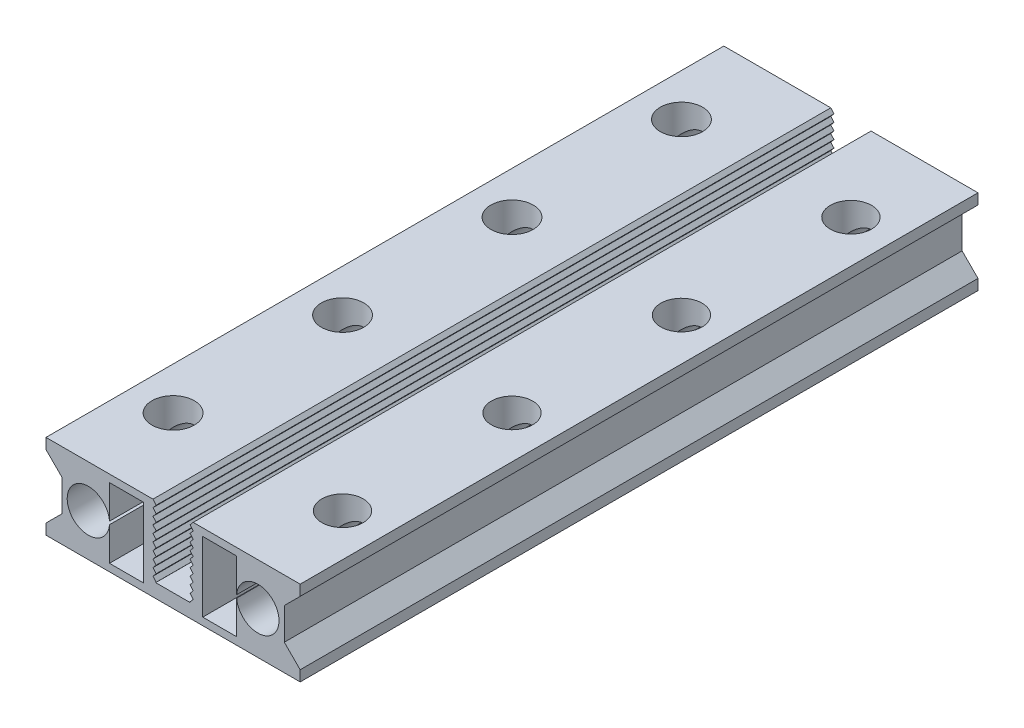
SolidWorks part; units mm, degrees
ref_plane "前视基准面" through (0, 0, 0) normal (0, 0, 1) x (1, 0, 0)
ref_plane "上视基准面" through (0, 0, 0) normal (0, 1, 0) x (1, 0, 0)
ref_plane "右视基准面" through (0, 0, 0) normal (1, 0, 0) x (0, 0, -1)
sketch "草图1" plane through (0, 0, 0) normal (0, 0, 1) x (1, 0, 0)
  line L0 (-12, 8) -> (-12, 7)
  line L1 (-12, 7) -> (-10.5, 5.5)
  line L2 (-10.5, 5.5) -> (-10.5, 2.5)
  line L3 (-10.5, 2.5) -> (-12, 1)
  line L4 (-12, 1) -> (-12, 0)
  line L5 (-12, 0) -> (12, 0)
  line L6 (12, 0) -> (12, 1)
  line L7 (12, 1) -> (10.5, 2.5)
  line L8 (10.5, 2.5) -> (10.5, 5.5)
  line L9 (10.5, 5.5) -> (12, 7)
  line L10 (12, 7) -> (12, 8)
  line L11 (12, 8) -> (1.9, 8)
  line L12 (0, 0) -> (0, 8) construction
  line L13 (-8, 4) -> (8, 4) construction
  line L14 (-1.9, 8) -> (-1.9, 1.3)
  line L15 (-6.005, 7.3) -> (-2.8, 7.3)
  line L16 (-6.005, 7.3) -> (-6.005, 4.1413)
  line L17 (-6.005, 0.7) -> (-2.8, 0.7)
  line L18 (-2.8, 7.3) -> (-2.8, 0.7)
  line L19 (-1.9, 1.3) -> (1.9, 1.3)
  line L20 (1.9, 1.3) -> (1.9, 8)
  line L21 (-1.9, 8) -> (-12, 8)
  line L22 (-6.005, 3.8587) -> (-6.005, 0.7)
  line L23 (2.8, 7.3) -> (6.005, 7.3)
  line L24 (2.8, 7.3) -> (2.8, 0.7)
  line L25 (2.8, 0.7) -> (6.005, 0.7)
  line L26 (6.005, 7.3) -> (6.005, 4.1413)
  line L27 (6.005, 3.8587) -> (6.005, 0.7)
  arc A0 (-6.005, 4.1413) -> (-6, 4) centre (-8, 4) ccw
  arc A1 (6.005, 3.8587) -> (6.005, 4.1413) centre (8, 4) ccw
  point P19 (10.5, 4)
  point P24 (-2.8, 4)
  point P27 (0, 1.3)
  dimension "D4" = 4
  dimension "D1" = 24
  dimension "D2" = 8
  dimension "D3" = 45
  dimension "D5" = 16
  dimension "D6" = 8
  dimension "D7" = 3
  dimension "D8" = 1
  dimension "D9" = 4
  dimension "D10" = 3.8
  dimension "D11" = 1.3
  dimension "D12" = 5.6
  dimension "D13" = 2.8
  dimension "D14" = 12.01
  dimension "D15" = 0.7
extrude "凸台-拉伸2" add sketch "草图1" along normal blind 64 contours L14 L21 L0 L1 L2 L3 L4 L5 L6 L7 L8 L9 L10 L11 L20 L19 A1 L27 L25 L24 L23 L26 A0 L16 L15 L18 L17 L22
sketch "草图3" plane through (0, 0, 64) normal (0, 0, 1) x (1, 0, 0)
  line L0 (-1.9, 8) -> (-1.6, 7.65)
  line L1 (-1.6, 7.65) -> (-1.9, 7.3)
  line L2 (-1.9, 8) -> (-1.9, 1.3) construction
  line L3 (-1.9, 7.3) -> (-1.9, 8)
  point P7 (-1.9, 7.65)
  dimension "D1" = 0.7
  dimension "D2" = 0.3
extrude "凸台-拉伸3" add sketch "草图3" against normal up to surface (64 mm away) up to face at (5.6025, 4, 0)
pattern_linear "阵列(线性)1" count 10 spacing 0.7 along (0, -1, 0) of "凸台-拉伸3"
mirror "镜向1" about plane through (0, 0, 0) normal (1, 0, 0) of "阵列(线性)1", "凸台-拉伸3"
sketch "草图4" plane through (0, 8, 0) normal (0, 1, 0) x (1, 0, 0)
  line L1 (12, 0) -> (1.9, 0) construction
  circle A0 centre (-8, -8) radius 2
  circle A1 centre (8, -8) radius 1.95
  dimension "D1" = 16
  dimension "D4" = 3.9
  dimension "D5" = 4
  dimension "D2" = 8
  dimension "D3" = 8
extrude "切除-拉伸1" cut sketch "草图4" against normal through all
pattern_linear "阵列(线性)2" count 4 spacing 16 along (0, 0, 1) of "切除-拉伸1"
equation "\"D13@草图1\"=\"D12@草图1\"/2"
